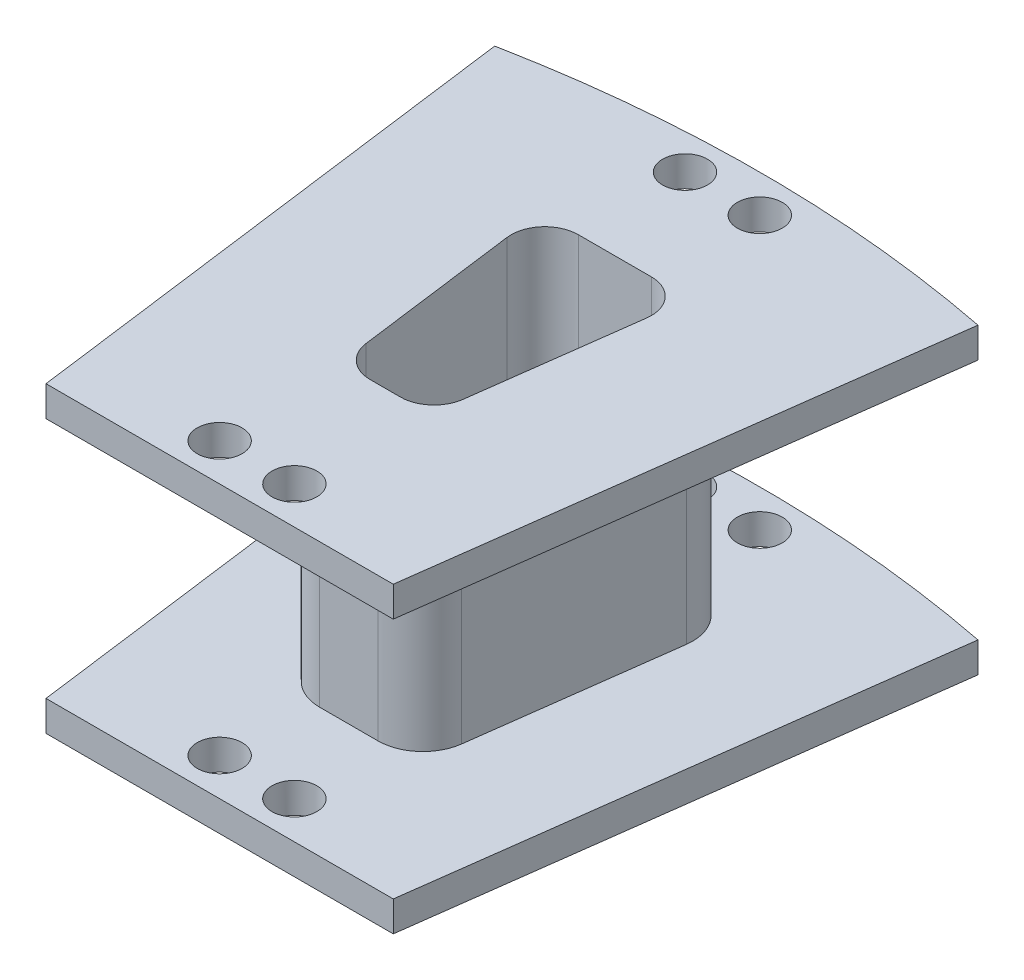
SolidWorks part; units mm, degrees
material "ABS"
ref_plane "Front Plane" through (0, 0, 0) normal (0, 0, 1) x (1, 0, 0)
ref_plane "Top Plane" through (0, 0, 0) normal (0, 1, 0) x (1, 0, 0)
ref_plane "Right Plane" through (0, 0, 0) normal (1, 0, 0) x (0, 0, -1)
sketch "Sketch1" plane through (0, 0, 0) normal (0, 1, 0) x (1, 0, 0)
  line L2 (-59.8461, 60.1876) -> (-43, -67.7712)
  line L3 (59.8461, 60.1876) -> (43, -67.7712)
  line L4 (0, 108.1999) -> (0, -114.8862) construction
  line L5 (-39.4678, 0) -> (38.1525, 0) construction
  line L6 (-9.0806, 62) -> (9.4787, 62) construction
  line L7 (-7.6404, -62) -> (7.7511, -62) construction
  line L8 (-43, -67.7712) -> (43, -67.7712)
  arc A2 (-59.8461, 60.1876) -> (59.8461, 60.1876) centre (0, -245) cw
  arc A3 (43, -67.7712) -> (-43, -67.7712) centre (0, -400) ccw construction
  circle A4 centre (-5, 62) radius 3 construction
  circle A5 centre (-5, -62) radius 3 construction
  circle A6 centre (5, -62) radius 3 construction
  circle A7 centre (5, 62) radius 3 construction
  point P24 (0, 66)
  point P25 (0, -65)
  dimension "D4" = 6
  dimension "D8" = 6
  dimension "D1" = 7.5
  dimension "D2" = 62
  dimension "D3" = 245
  dimension "D5" = 5
  dimension "D6" = 3
  dimension "D7" = 4
  dimension "D9" = 400
  dimension "D10" = 43
extrude "Boss-Extrude1" add sketch "Sketch1" along normal blind 7.5
sketch "Sketch2" plane through (0, 7.5, 0) normal (0, 1, 0) x (1, 0, 0)
  line L2 (-26.2412, 34.772) -> (-16.954, -35.7712)
  line L8 (16.954, -35.7712) -> (26.2412, 34.772)
  line L10 (-59.8461, 60.1876) -> (-43, -67.7712)
  line L11 (43, -67.7712) -> (59.8461, 60.1876)
  line L14 (-59.8461, 60.1876) -> (-43, -67.7712) construction
  line L15 (43, -67.7712) -> (59.8461, 60.1876) construction
  line L16 (-16.954, -35.7712) -> (16.954, -35.7712)
  line L19 (-43, -67.7712) -> (43, -67.7712)
  line L20 (-43, -67.7712) -> (43, -67.7712)
  arc A2 (26.2412, 34.772) -> (-26.2412, 34.772) centre (0, -245) ccw
  arc A8 (16.954, -35.7712) -> (-16.954, -35.7712) centre (0, -462.2148) ccw construction
  arc A10 (59.8461, 60.1876) -> (-59.8461, 60.1876) centre (0, -245) ccw
  arc A22 (59.8461, 60.1876) -> (-59.8461, 60.1876) centre (0, -245) ccw construction
  arc A28 (43, -67.7712) -> (-43, -67.7712) centre (0, -462.2148) ccw construction
  dimension "D3" = 32
  dimension "D1" = 0
  dimension "D2" = 30
extrude "Boss-Extrude2" add sketch "Sketch2" along normal blind 60 contours L8 A2 L2 L16
ref_plane "Plane1" through (0, 37.5, 0) normal (0, 1, 0) x (1, 0, 0)
mirror "Mirror1" about plane through (0, 37.5, 0) normal (0, 1, 0) of "Boss-Extrude1"
scale "Scale1" scale about centroid uniform scaling yes scale factor 0.27
fillet "Fillet1" radius 3 4 edges at (-7.0851, 37.5, -10.959) (7.0851, 37.5, -10.959) (4.5776, 37.5, 8.0877) (-4.5776, 37.5, 8.0877)
sketch "Sketch3" plane through (0, 47.625, 0) normal (0, 1, 0) x (1, 0, 0)
  line L0 (-4.6679, 7.155) -> (-3.2394, -3.696)
  line L1 (3.2394, -3.696) -> (4.6679, 7.155)
  line L2 (-16.1584, 17.8212) -> (-11.61, -16.7277)
  line L3 (11.61, -16.7277) -> (16.1584, 17.8212)
  line L4 (-16.1584, 17.8212) -> (-11.61, -16.7277) construction
  line L5 (11.61, -16.7277) -> (16.1584, 17.8212) construction
  line L6 (-4.9405, 9.2254) -> (-2.9333, -6.0209) construction
  line L7 (2.9333, -6.0209) -> (4.9405, 9.2254) construction
  line L8 (0, 0) -> (0, -26.3711) construction
  line L9 (0, 0) -> (7.3155, 0) construction
  line L10 (0, 0) -> (0, 24.8713) construction
  line L11 (-11.61, -16.7277) -> (11.61, -16.7277)
  line L12 (-11.61, -16.7277) -> (11.61, -16.7277)
  line L13 (0, 19.3905) -> (-8.1289, 19.3905) construction
  line L14 (-2.4372, 9.6987) -> (2.4372, 9.6987)
  line L15 (-1.0086, -5.6523) -> (1.0086, -5.6523)
  arc A2 (16.1584, 17.8212) -> (-16.1584, 17.8212) centre (0, -64.5795) ccw
  circle A3 centre (2.5, -14.2277) radius 1.5
  arc A4 (16.1584, 17.8212) -> (-16.1584, 17.8212) centre (0, -64.5795) ccw construction
  arc A6 (4.9405, 9.2254) -> (-4.9405, 9.2254) centre (0, -64.5795) ccw construction
  arc A7 (-4.6679, 7.155) -> (-2.4372, 9.6987) centre (-2.4372, 7.4487) cw
  arc A8 (2.4372, 9.6987) -> (4.6679, 7.155) centre (2.4372, 7.4487) cw
  arc A9 (2.9333, -6.0209) -> (-2.9333, -6.0209) centre (0, -106.2451) ccw construction
  arc A10 (-3.2394, -3.696) -> (-1.0086, -5.6523) centre (-1.0086, -3.4023) ccw
  arc A11 (3.2394, -3.696) -> (1.0086, -5.6523) centre (1.0086, -3.4023) cw
  circle A12 centre (-2.5, -14.2277) radius 1.5
  circle A13 centre (-2.5, 16.8905) radius 1.5
  arc A14 (11.61, -16.7277) -> (-11.61, -16.7277) centre (0, -106.2451) ccw construction
  circle A15 centre (2.5, 16.8905) radius 1.5
  point P39 (0, 9.6987)
  point P40 (0, -5.6523)
  dimension "D3" = 2.25
  dimension "D4" = 2.25
  dimension "D5" = 2.5
  dimension "D6" = 3
  dimension "D8" = 5
  dimension "D9" = 3
  dimension "D7" = 2.5
  dimension "D11" = 15.351
  dimension "D12" = 5.6523
  dimension "D13" = 3.4023
  dimension "D1" = 0
  dimension "D2" = 10
extrude "Cut-Extrude1" cut sketch "Sketch3" against normal through all both and the other way through all contours A11 L1 A8 L14 A7 L0 A10 L15 | A15 | A13 | A12 | A3
